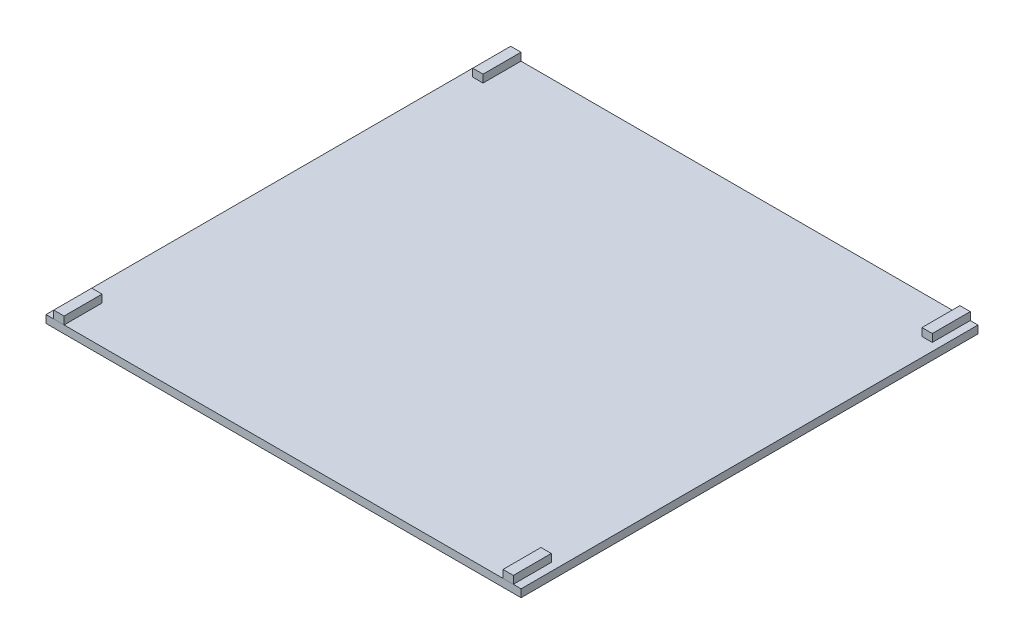
SolidWorks part; units mm, degrees
ref_plane "Спереди" through (0, 0, 0) normal (0, 0, 1) x (1, 0, 0)
ref_plane "Сверху" through (0, 0, 0) normal (0, 1, 0) x (1, 0, 0)
ref_plane "Справа" through (0, 0, 0) normal (1, 0, 0) x (0, 0, -1)
sketch "Эскиз1" plane through (0, 0, 0) normal (0, 1, 0) x (1, 0, 0)
  line L1 (46, -44.245) -> (-46, -44.245)
  line L2 (46, -44.245) -> (46, 44.245)
  line L3 (46, 44.245) -> (-46, 44.245)
  line L4 (-46, -44.245) -> (-46, 44.245)
  line L5 (46, -44.245) -> (-46, 44.245) construction
  line L6 (46, 44.245) -> (-46, -44.245) construction
  point P0 (0, 0)
  dimension "D1" = 88.49
  dimension "D2" = 92
extrude "Бобышка-Вытянуть1" add sketch "Эскиз1" along normal blind 1.5
sketch "Эскиз2" plane through (0, 1.5, 0) normal (0, 1, 0) x (1, 0, 0)
  line L0 (-44.5, 44.245) -> (-44.5, -44.245) construction
  line L1 (46, 44.245) -> (-46, 44.245) construction
  line L2 (-46, -44.245) -> (46, -44.245) construction
  line L3 (44.5, 44.245) -> (44.5, 36.8905) construction
  line L4 (-46, 44.245) -> (-46, -44.245) construction
  line L5 (46, -44.245) -> (46, 44.245) construction
  line L6 (42.5, 36.8905) -> (42.5, 44.245)
  line L7 (44.5, -44.245) -> (42.5, -44.245)
  line L8 (44.5, -44.245) -> (44.5, -36.8905)
  line L9 (44.5, 44.245) -> (42.5, 44.245)
  line L10 (42.5, -44.245) -> (42.5, -36.8905)
  line L11 (-44.5, 44.245) -> (-42.5, 44.245)
  line L12 (-44.5, 44.245) -> (-44.5, 19.245)
  line L13 (44.5, 36.8905) -> (44.5, 44.245)
  line L14 (-42.5, 44.245) -> (-42.5, 36.8905)
  line L15 (-44.5, -44.245) -> (-42.5, -44.245)
  line L16 (-44.5, -44.245) -> (-44.5, -36.8905)
  line L17 (-44.5, -11.245) -> (-42.5, -11.245)
  line L18 (-42.5, -44.245) -> (-42.5, -35.2325)
  line L19 (44.5, -36.8905) -> (42.5, -36.8905)
  line L20 (44.5, -36.8905) -> (44.5, -44.245) construction
  line L21 (44.5, 36.8905) -> (42.5, 36.8905)
  line L22 (-44.5, -11.245) -> (-44.5, 36.8905)
  line L25 (-42.5, 36.8905) -> (-44.5, 36.8905)
  line L26 (-42.5, -36.8905) -> (-44.5, -36.8905)
  line L27 (-42.5, -35.2325) -> (-44.5, -36.8905) construction
  point P20 (0, 0)
  point P27 (-44.5, 36.8905)
  line M10 (-46, -44.245) -> (46, -44.245)
  line M12 (46, 44.245) -> (-46, 44.245)
  dimension "D1" = 1.5
  dimension "D2" = 1.5
  dimension "D3" = 2
  dimension "D4" = 2
  dimension "D6" = 33
  dimension "D7" = 2
extrude "Бобышка-Вытянуть2" add sketch "Эскиз2" along normal blind 1.5 separate body contours L21 L13 L6 M12 | L25 L14 L12 M12 | L18 L26 L16 M10 | L8 L19 L10 M10
